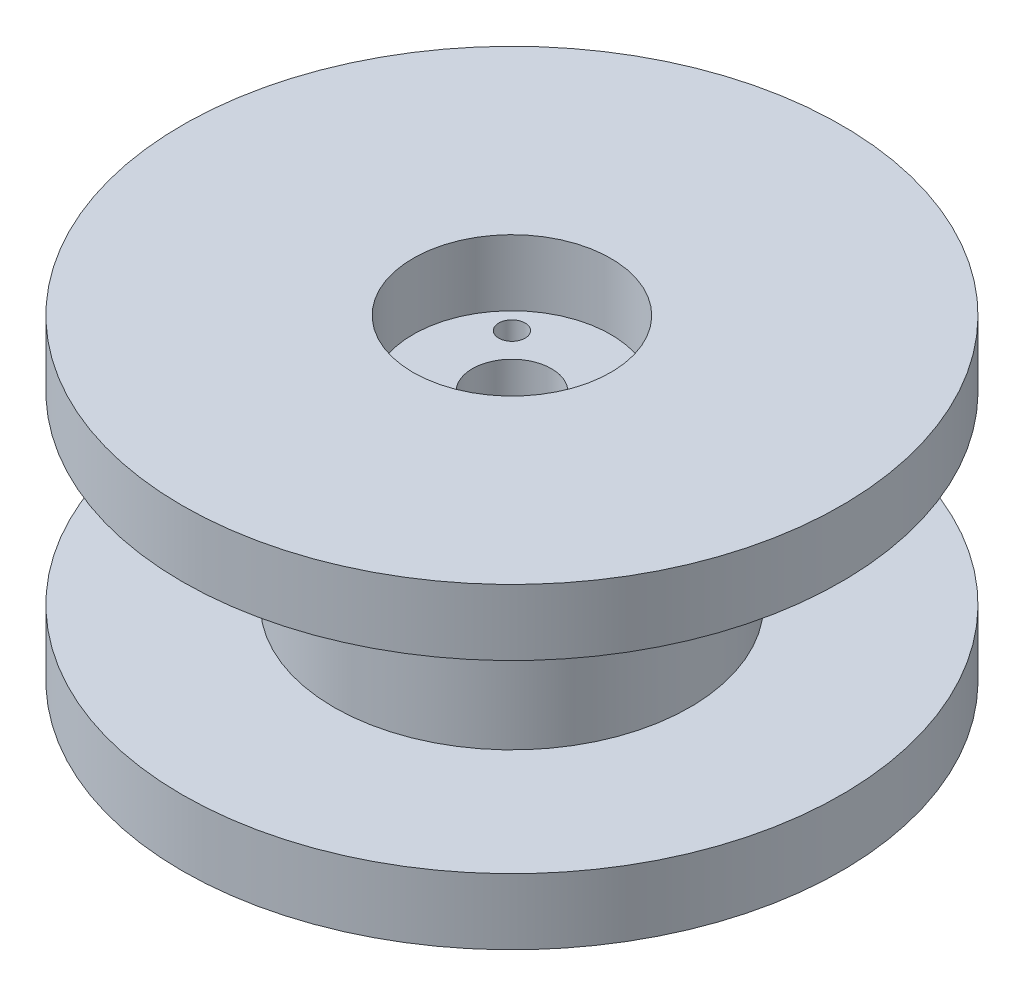
SolidWorks part; units mm, degrees
ref_plane "Front Plane" through (0, 0, 0) normal (0, 0, 1) x (1, 0, 0)
ref_plane "Top Plane" through (0, 0, 0) normal (0, 1, 0) x (1, 0, 0)
ref_plane "Right Plane" through (0, 0, 0) normal (1, 0, 0) x (0, 0, -1)
sketch "Sketch1" plane through (0, 0, 0) normal (1, 0, 0) x (0, 0, -1)
  line L0 (0, 7) -> (0, -7)
  line L1 (-7.5, 12) -> (-25, 12)
  line L2 (-25, 12) -> (-25, 7)
  line L3 (-25, 7) -> (-13.5, 7)
  line L5 (-13.5, -7) -> (-13.5, 7)
  line L9 (-7.5, 12) -> (-7.5, 7)
  line L10 (-7.5, 7) -> (0, 7)
  line L11 (-13.5, 0) -> (0, 0) construction
  line L12 (-7.5, -7) -> (0, -7)
  line L13 (-7.5, -12) -> (-7.5, -7)
  line L14 (-25, -7) -> (-13.5, -7)
  line L15 (-25, -12) -> (-25, -7)
  line L16 (-7.5, -12) -> (-25, -12)
  point P12 (0, 0)
  dimension "D1" = 7.5
  dimension "D2" = 5
  dimension "D3" = 25
  dimension "D4" = 12
  dimension "D5" = 13.5
  dimension "D6" = 5
revolve "Revolve1" add sketch "Sketch1" angle 360 about L0
sketch "Sketch2" plane through (0, -7, 0) normal (0, -1, 0) x (1, 0, 0)
  line L0 (4, -4) -> (-4, 4) construction
  line L1 (-4, -4) -> (4, 4) construction
  circle A0 centre (0, 0) radius 3
  circle A1 centre (4, -4) radius 1
  circle A2 centre (-4, -4) radius 1
  circle A3 centre (-4, 4) radius 1
  circle A4 centre (4, 4) radius 1
  point P2 (0, 0)
  point P4 (0, 0)
  point P7 (0, 0)
  point P9 (0, 0)
  point P13 (0, 0)
  dimension "D1" = 6
  dimension "D2" = 2
  dimension "D3" = 8
  dimension "D4" = 8
extrude "Cut-Extrude1" cut sketch "Sketch2" against normal through all both and the other way through all
